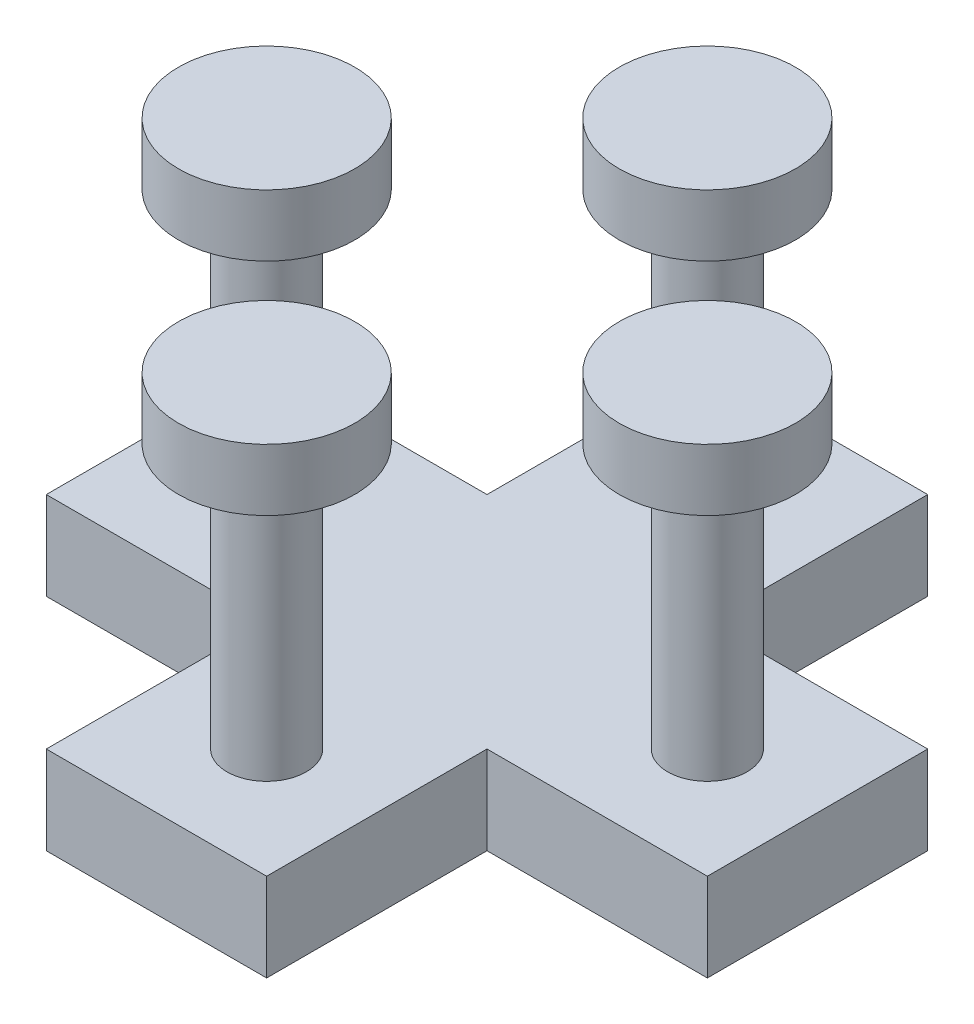
SolidWorks part; units mm, degrees
ref_plane "Front Plane" through (0, 0, 0) normal (0, 0, 1) x (1, 0, 0)
ref_plane "Top Plane" through (0, 0, 0) normal (0, 1, 0) x (1, 0, 0)
ref_plane "Right Plane" through (0, 0, 0) normal (1, 0, 0) x (0, 0, -1)
sketch "Sketch1" plane through (0, 0, 0) normal (0, 1, 0) x (1, 0, 0)
  line L0 (-8.3487, -10.4521) -> (-8.3487, -4.1021)
  line L1 (-8.3487, -4.1021) -> (-1.9987, -4.1021)
  line L2 (-1.9987, -4.1021) -> (-1.9987, -10.4521)
  line L3 (-1.9987, -10.4521) -> (4.3513, -10.4521)
  line L4 (4.3513, -10.4521) -> (4.3513, -16.8021)
  line L5 (4.3513, -16.8021) -> (-1.9987, -16.8021)
  line L6 (-1.9987, -16.8021) -> (-1.9987, -23.1521)
  line L7 (-1.9987, -23.1521) -> (-8.3487, -23.1521)
  line L8 (-8.3487, -23.1521) -> (-8.3487, -16.8021)
  line L9 (-8.3487, -16.8021) -> (-14.6987, -16.8021)
  line L10 (-14.6987, -16.8021) -> (-14.6987, -10.4521)
  line L11 (-14.6987, -10.4521) -> (-8.3487, -10.4521)
  dimension "D1" = 6.35
  dimension "D2" = 6.35
  dimension "D3" = 6.35
  dimension "D4" = 6.35
  dimension "D5" = 6.35
  dimension "D6" = 6.35
  dimension "D7" = 6.35
  dimension "D8" = 6.35
  dimension "D9" = 6.35
  dimension "D10" = 6.35
extrude "body" add sketch "Sketch1" along normal blind 2.54
sketch "Sketch2" plane through (0, 2.54, 0) normal (0, 1, 0) x (1, 0, 0)
  line L0 (-8.3487, -10.4521) -> (-14.6987, -10.4521) construction
  line L1 (-1.9987, -23.1521) -> (-1.9987, -16.8021) construction
  line L2 (-1.9987, -16.8021) -> (4.3513, -16.8021) construction
  line L3 (-1.9987, -10.4521) -> (-1.9987, -4.1021) construction
  line L4 (-1.9987, -4.1021) -> (-8.3487, -4.1021) construction
  line L5 (-14.6987, -10.4521) -> (-14.6987, -16.8021) construction
  line L6 (-8.3487, -23.1521) -> (-1.9987, -23.1521) construction
  line L7 (4.3513, -16.8021) -> (4.3513, -10.4521) construction
  circle A0 centre (-5.1737, -7.2771) radius 1.143
  circle A1 centre (1.1763, -13.6271) radius 1.143
  circle A2 centre (-5.1737, -19.9771) radius 1.143
  circle A3 centre (-11.5237, -13.6271) radius 1.143
  dimension "D1" = 2.286
  dimension "D2" = 2.286
  dimension "D3" = 2.286
  dimension "D4" = 2.286
  dimension "D5" = 3.175
  dimension "D6" = 3.175
  dimension "D7" = 3.175
  dimension "D8" = 3.175
  dimension "D9" = 3.175
  dimension "D10" = 3.175
  dimension "D11" = 3.175
  dimension "D12" = 3.175
extrude "flag" add sketch "Sketch2" along normal blind 7.62
ref_point "centre 1"
ref_point "centre 2"
ref_point "centre 3"
ref_point "centre 4"
ref_plane "plane o' feet" through (0, 10.16, 0) normal (0, 1, 0) x (1, 0, 0)
sketch "Sketch3" plane through (0, 10.16, 0) normal (0, 1, 0) x (1, 0, 0)
  circle A0 centre (-5.1737, -7.2771) radius 2.54
  circle A1 centre (-11.5237, -13.6271) radius 2.54
  circle A2 centre (-5.1737, -19.9771) radius 2.54
  circle A3 centre (1.1763, -13.6271) radius 2.54
  dimension "D1" = 5.08
  dimension "D2" = 5.08
  dimension "D3" = 5.08
  dimension "D4" = 5.08
extrude "feet" add sketch "Sketch3" along normal blind 1.778
